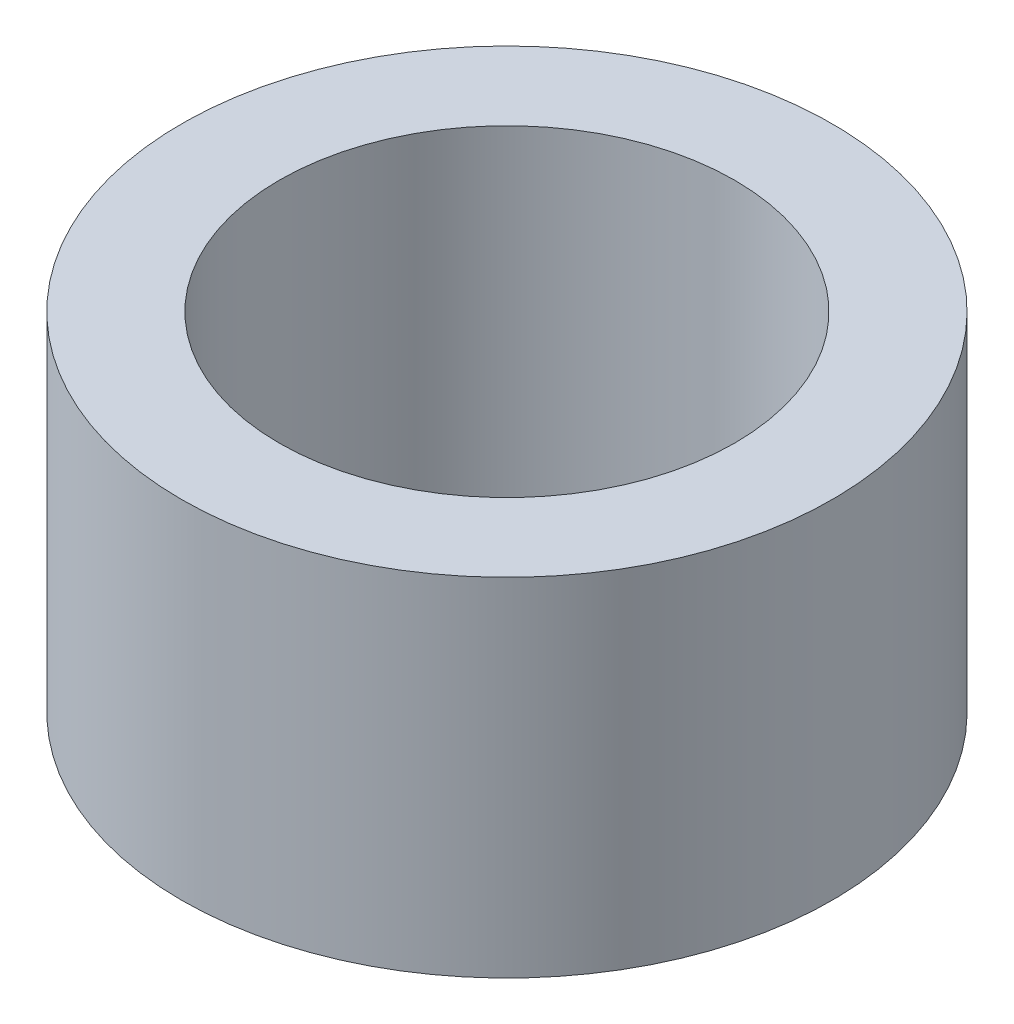
SolidWorks part; units mm, degrees
material "Custom Plastic"
ref_plane "X-Y Datum" through (0, 0, 0) normal (0, 0, 1) x (1, 0, 0)
ref_plane "X-Z Datum" through (0, 0, 0) normal (0, 1, 0) x (1, 0, 0)
ref_plane "Y-Z Datum" through (0, 0, 0) normal (1, 0, 0) x (0, 0, -1)
sketch "Sketch1" plane through (0, 0, 0) normal (0, 1, 0) x (1, 0, 0)
  circle A0 centre (0, 0) radius 2.8575
  circle A1 centre (0, 0) radius 2
  dimension "D1" = 4
  dimension "D2" = 5.715
extrude "Boss-Extrude1" add sketch "Sketch1" against normal blind 3.048
